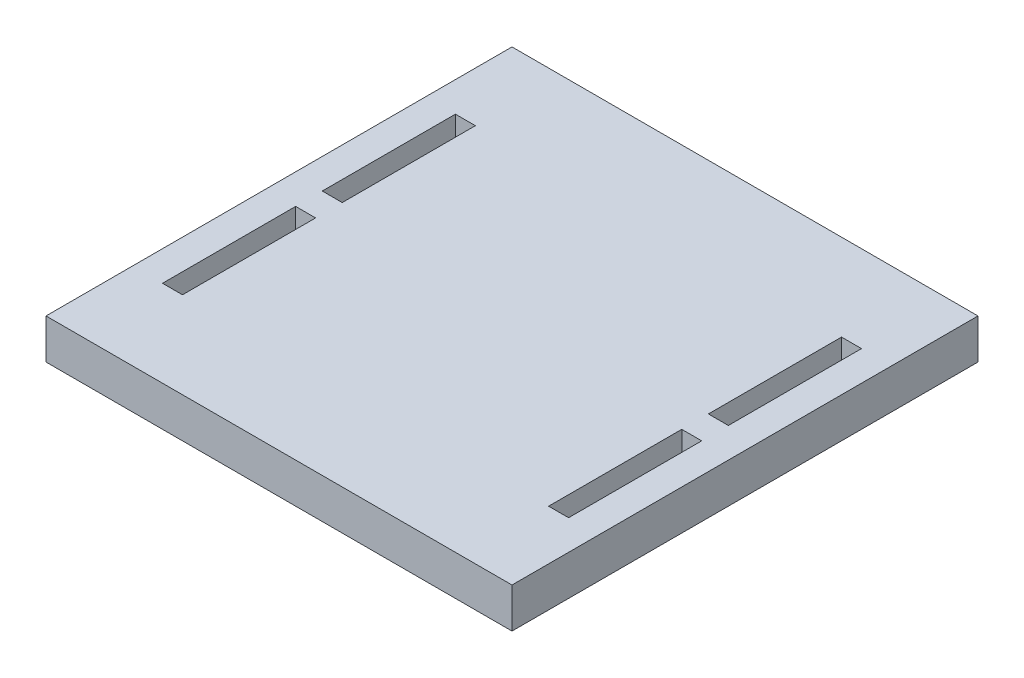
SolidWorks part; units mm, degrees
ref_plane "前视基准面" through (0, 0, 0) normal (0, 0, 1) x (1, 0, 0)
ref_plane "上视基准面" through (0, 0, 0) normal (0, 1, 0) x (1, 0, 0)
ref_plane "右视基准面" through (0, 0, 0) normal (1, 0, 0) x (0, 0, -1)
other "Configuration Table"
sketch "草图1" plane through (0, 0, 0) normal (0, 1, 0) x (1, 0, 0)
  line L0 (35, 0) -> (35, -70)
  line L1 (0, 0) -> (70, 0)
  line L2 (0, 0) -> (0, -70)
  line L3 (0, -70) -> (70, -70)
  line L4 (70, 0) -> (70, -70)
  line L9 (0, -35) -> (70, -35)
  line L28 (4.5, -13) -> (7.5, -13)
  line L29 (4.5, -13) -> (4.5, -33)
  line L30 (4.5, -33) -> (7.5, -33)
  line L31 (7.5, -13) -> (7.5, -33)
  line L36 (4.5, -37) -> (7.5, -37)
  line L37 (7.5, -57) -> (7.5, -37)
  line L38 (4.5, -57) -> (7.5, -57)
  line L39 (4.5, -57) -> (4.5, -37)
  line L40 (65.5, -57) -> (65.5, -37)
  line L41 (65.5, -57) -> (62.5, -57)
  line L42 (62.5, -57) -> (62.5, -37)
  line L43 (65.5, -37) -> (62.5, -37)
  line L52 (65.5, -33) -> (62.5, -33)
  line L53 (62.5, -13) -> (62.5, -33)
  line L54 (65.5, -13) -> (62.5, -13)
  line L55 (65.5, -13) -> (65.5, -33)
  dimension "D1" = 70
  dimension "D2" = 70
  dimension "D3" = 2
  dimension "D4" = 3
  dimension "D5" = 20
extrude "凸台-拉伸1" add sketch "草图1" along normal blind 6
